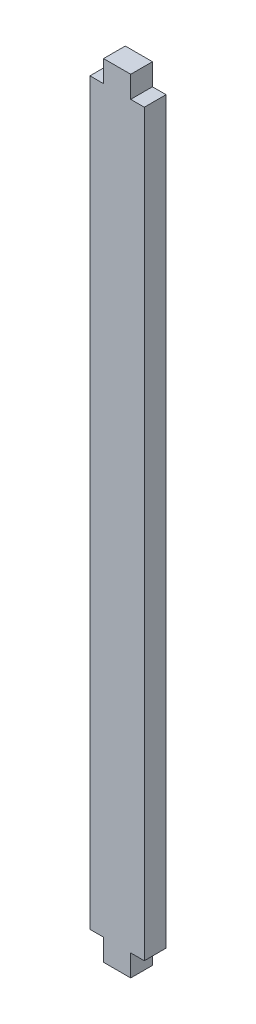
SolidWorks part; units mm, degrees
ref_plane "Front Plane" through (0, 0, 0) normal (0, 0, 1) x (1, 0, 0)
ref_plane "Top Plane" through (0, 0, 0) normal (0, 1, 0) x (1, 0, 0)
ref_plane "Right Plane" through (0, 0, 0) normal (1, 0, 0) x (0, 0, -1)
sketch "Sketch2" plane through (0, 0, 0) normal (0, 0, 1) x (1, 0, 0)
  line L1 (0, 0) -> (12.7, 0)
  line L2 (0, 0) -> (0, 182.88)
  line L3 (0, 182.88) -> (12.7, 182.88)
  line L4 (12.7, 0) -> (12.7, 182.88)
  dimension "D1" = 12.7
  dimension "D2" = 182.88
extrude "Boss-Extrude1" add sketch "Sketch2" along normal blind 5.08
sketch "Sketch3" plane through (0, 0, 5.08) normal (0, 0, 1) x (1, 0, 0)
  line L1 (0, 182.88) -> (3.175, 182.88)
  line L2 (0, 182.88) -> (0, 177.8)
  line L3 (0, 177.8) -> (3.175, 177.8)
  line L4 (3.175, 182.88) -> (3.175, 177.8)
  line L5 (12.7, 182.88) -> (9.525, 182.88)
  line L6 (12.7, 182.88) -> (12.7, 177.8)
  line L7 (12.7, 177.8) -> (9.525, 177.8)
  line L8 (9.525, 182.88) -> (9.525, 177.8)
  line L9 (0, 0) -> (3.175, 0)
  line L10 (0, 0) -> (0, 5.08)
  line L11 (0, 5.08) -> (3.175, 5.08)
  line L12 (3.175, 0) -> (3.175, 5.08)
  line L13 (12.7, 0) -> (9.525, 0)
  line L14 (12.7, 0) -> (12.7, 5.08)
  line L15 (12.7, 5.08) -> (9.525, 5.08)
  line L16 (9.525, 0) -> (9.525, 5.08)
  dimension "D1" = 3.175
  dimension "D2" = 5.08
extrude "Cut-Extrude1" cut sketch "Sketch3" against normal through all
equation "\"FoamCore\" = \".2\""
equation "\"MDF\" = \".2\""
equation "\"GMaterial\"= \".2\""
equation "\"PVCMountDiameter\" = \"0.5in\""
equation "\"PVCMountDistanceToEdge\" = \"0.5\""
equation "\"PVCThickness\" = \"0.13in\""
equation "\"PVCDiameter\" = 1.5in"
equation "\"BaseWidth\" = \"8in\""
equation "\"BaseLength\" = \"10in\""
equation "\"BallDiameter\" = \"1.57in\""
equation "\"BaseGap\" = \"4in\""
equation "\"FunnelTopDiameter\" = \"8in\""
equation "\"FunnelTopDepth\" = \"3.5in\""
equation "\"BallGap\" = \"0.1in\""
equation "\"FunnelLength\" = 3in"
equation "\"FunnelMaterial\" = 0.1in"
equation "\"FunnelLowerDiameter\" = 1.9in"
equation "\"FunnelDepth\" = 1.5in"
equation "\"FunnelBendLength\" = 2*pi*\"FunnelLowerDiameter\"/2*135"
equation "\"AmmoFeederLength\" = 1.5in + 76mm"
equation "\"WheelThickness\" = 0.5in"
equation "\"LauncherWheelDiameter\" = 76mm"
equation "\"MotorFrontLength\" = 0.95in"
equation "\"MotorBodyTotalLength\" = 2.03in"
equation "\"MotorFrontDiameter\" = 1.5in"
equation "\"MotorLowerDriveshaftDiameter\" = 0.46in"
equation "\"MotorLowerDriveshaftThickness\" = 0.25in"
equation "\"MotorFullDriveshaftLength\" = 0.78in"
equation "\"MotorDriveshaftDiameter\" = 0.23in"
equation "\"MotorDriveshaftFlatThickness\" = 0.2in"
equation "\"MotorRearDiameter\" = 31.9mm"
equation "\"MotorDriveshaftBottomToTop\" = 31.1mm"
equation "\"MotorFlatDriveshaftLength\" = 11.7mm"
equation "\"MotorDistanceBetweenLowerandTopHoles\" = 0.5in"
equation "\"MotorMountsDistanceFromEdge\" = 0.06in"
equation "\"MotorScrewMountDiameter\" = 0.1in"
equation "\"MotorScrewMountDepth\" = 0.13in"
equation "\"HBRidgeScrewHoleDeep\" = 0.18in"
equation "\"MotorMountWidth\" = \"1.61in\""
equation "\"MotorMountLength\" = \"1.58in\""
equation "\"MotorMountToEdgeGap\" = \"3.3mm\""
equation "\"MotorMountToInsideEdgeGap\" = \"6.5mm\""
equation "\"MotorMountToMountWidthGap\" = \"25.8mm\""
equation "\"MotorMountToMountLengthGap\" = \"20.5mm\""
equation "\"MotorMountMaterialThickness\" = 1.6mm"
equation "\"MotorMountBaseScrewholeDiameter\" = 3.8mm"
equation "\"MotorMountBaseDistancebetweenHoles\" = 0.8in"
equation "\"MotorMountHeight\" = 1.82in"
equation "\"HBridgeWidth\" = 2.25in"
equation "\"HBridgeLength\" = 1.40in"
equation "\"UnoWidth\" = 3.13in"
equation "\"UnoLength\" = 3.06in"
equation "\"BatteryWidth\" = 1.15in"
equation "\"BatteryLength\" = 3.86in"
equation "\"ScrewDiameter\" = 2.7mm"
equation "\"MotorMountFaceScrewtoBase\" = 0.46in"
equation "\"MotorMountFaceDistanceBetweenScrews\" = 0.95in"
equation "\"MotorMountFaceMiddletoEdge\" = 0.16in"
equation "\"MotorMountFaceBottomtoEdge\" = 0.42in"
equation "\"MotorMountCenterholeHeight\" = 1.04in"
equation "\"MotorMountCenterholetoEdge\" = 0.25in"
equation "\"MovingWheelDiameter\" = 76mm"
equation "\"MovingWheelThickness\" = 0.5in"
equation "\"AmmoFeederCutoffLength\" = \"MovingWheelDiameter\""
equation "\"BraceLength\" = 0.5in"
equation "\"BraceVerticalOffset\" = 3.5in"
equation "\"BraceHorizontalOffset\" = 2.5in"
equation "\"D1@Sketch2\"=\"BraceLength\""
equation "\"BaseToBaseDistance\" = 7in"
equation "\"D2@Sketch2\"=\"BaseToBaseDistance\"+\"MDF\""
equation "\"D1@Boss-Extrude1\"=\"MDF\""
equation "\"D1@Sketch3\"=\"BraceLength\" /4"
equation "\"D2@Sketch3\"=\"MDF\""
